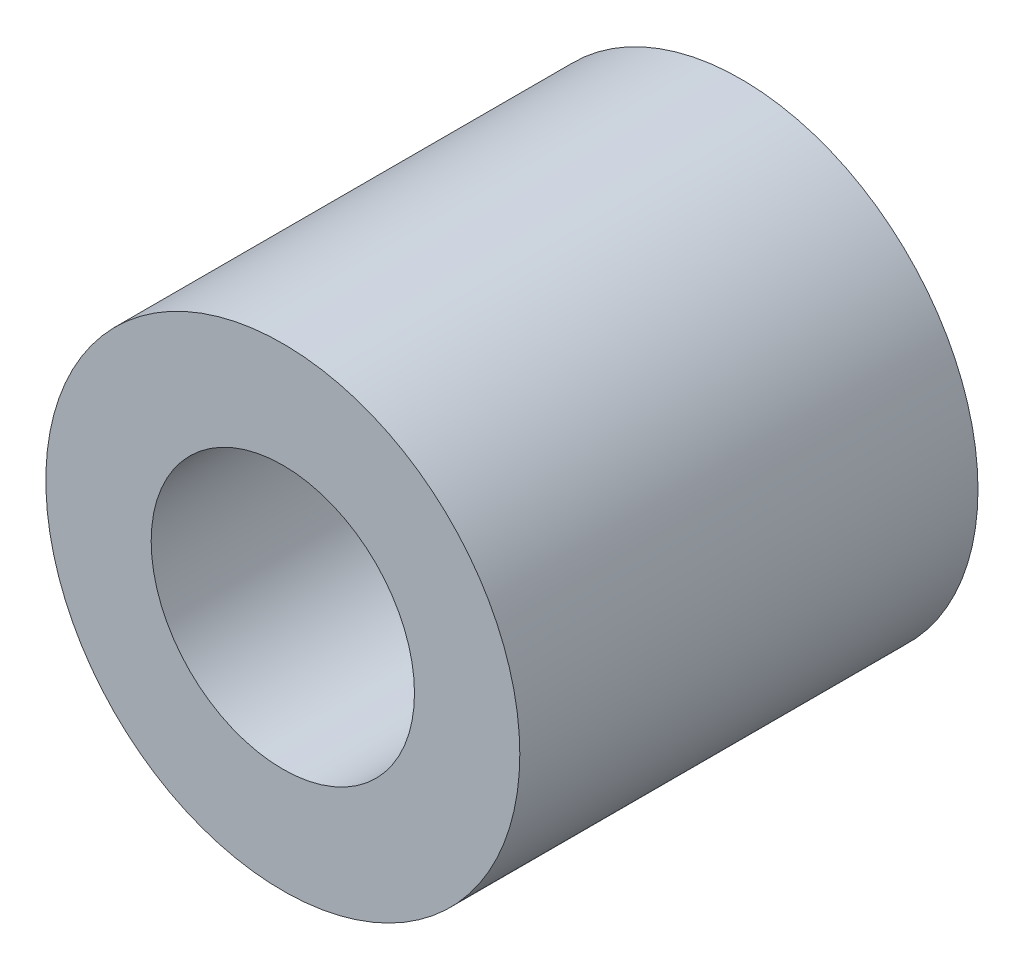
SolidWorks part; units mm, degrees
ref_plane "Front Plane" through (0, 0, 0) normal (0, 0, 1) x (1, 0, 0)
ref_plane "Top Plane" through (0, 0, 0) normal (0, 1, 0) x (1, 0, 0)
ref_plane "Right Plane" through (0, 0, 0) normal (1, 0, 0) x (0, 0, -1)
sketch "Sketch2" plane through (0, 0, 0) normal (0, 0, 1) x (1, 0, 0)
  circle A0 centre (0, 0) radius 2.5
  circle A1 centre (0, 0) radius 4.5
  dimension "D1" = 5
  dimension "D2" = 9
extrude "Boss-Extrude1" add sketch "Sketch2" along normal blind 20
sketch "Sketch3" plane through (0, 0, 20) normal (0, 0, 1) x (1, 0, 0)
  circle A2 centre (0, 0) radius 4.5
  circle A3 centre (0, 0) radius 4.5
  dimension "D1" = 0
extrude "Cut-Extrude1" cut sketch "Sketch3" against normal blind 11.3
